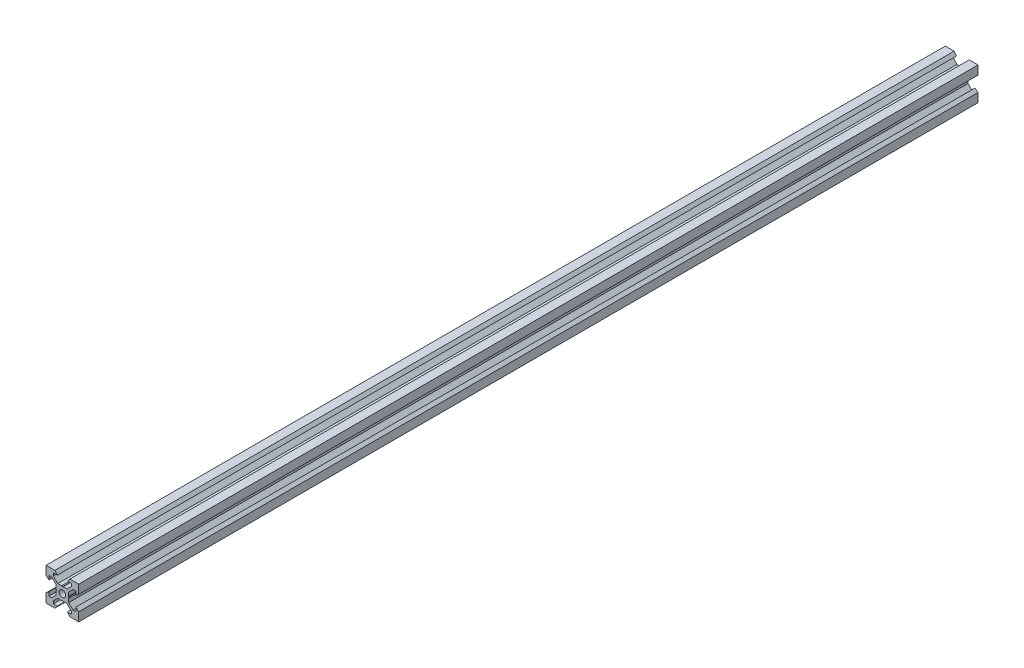
SolidWorks part; units mm, degrees
ref_plane "Front Plane" through (0, 0, 0) normal (0, 0, 1) x (1, 0, 0)
ref_plane "Top Plane" through (0, 0, 0) normal (0, 1, 0) x (1, 0, 0)
ref_plane "Right Plane" through (0, 0, 0) normal (1, 0, 0) x (0, 0, -1)
sketch "Sketch1" plane through (0, 0, 0) normal (0, 0, 1) x (1, 0, 0)
  line L0 (10, 10) -> (4.6104, 10) construction
  line L1 (10, 10) -> (10, 4.6104) construction
  line L2 (10, -10) -> (10, -4.6104) construction
  line L3 (10, -10) -> (4.6104, -10) construction
  line L4 (10, 10) -> (10, 4.6104)
  line L5 (6.5607, 5.5) -> (8.2, 5.5)
  line L6 (5.5, 8.2) -> (5.5, 6.5607)
  line L7 (10, 10) -> (4.6104, 10)
  line L8 (10, 10) -> (10, 4.6104)
  line L9 (6.5607, 5.5) -> (3.9, 2.8393)
  line L10 (5.5, 6.5607) -> (2.8393, 3.9)
  line L11 (10, 4.6104) -> (8.2, 3.1)
  line L12 (4.6104, 10) -> (3.1, 8.2)
  line L13 (8.2, 3.1) -> (8.2, 5.5)
  line L14 (3.1, 8.2) -> (5.5, 8.2)
  line L15 (-6.5607, 5.5) -> (-8.2, 5.5)
  line L16 (6.5607, -5.5) -> (8.2, -5.5)
  line L17 (3.1, -8.2) -> (5.5, -8.2)
  line L18 (8.2, -3.1) -> (8.2, -5.5)
  line L19 (4.6104, -10) -> (3.1, -8.2)
  line L20 (10, -4.6104) -> (8.2, -3.1)
  line L21 (0.5196, -3.9) -> (0, -3.6)
  line L22 (0.5196, 3.9) -> (0, 3.6)
  line L23 (3.6, 0) -> (3.9, -0.5196)
  line L24 (3.9, 0.5196) -> (3.6, 0)
  line L25 (3.9, 0.5196) -> (3.9, 2.8393)
  line L26 (2.8393, 3.9) -> (0.5196, 3.9)
  line L27 (3.9, -2.8393) -> (3.9, -0.5196)
  line L28 (2.8393, -3.9) -> (0.5196, -3.9)
  line L29 (5.5, -6.5607) -> (2.8393, -3.9)
  line L30 (6.5607, -5.5) -> (3.9, -2.8393)
  line L31 (10, -10) -> (10, -4.6104)
  line L32 (10, -10) -> (4.6104, -10)
  line L33 (5.5, -8.2) -> (5.5, -6.5607)
  line L34 (-6.5607, -5.5) -> (-8.2, -5.5)
  line L35 (10, -10) -> (10, -4.6104)
  line L36 (0, 0) -> (0, 8.2) construction
  line L37 (-10, -10) -> (-4.6104, -10) construction
  line L38 (-10, -10) -> (-10, -4.6104) construction
  line L39 (-10, 10) -> (-10, 4.6104) construction
  line L40 (-10, 10) -> (-4.6104, 10) construction
  line L41 (-10, -10) -> (-10, -4.6104)
  line L43 (-5.5, -8.2) -> (-5.5, -6.5607)
  line L44 (-10, -10) -> (-4.6104, -10)
  line L45 (-10, -10) -> (-10, -4.6104)
  line L46 (-6.5607, -5.5) -> (-3.9, -2.8393)
  line L47 (-5.5, -6.5607) -> (-2.8393, -3.9)
  line L48 (-2.8393, -3.9) -> (-0.5196, -3.9)
  line L49 (-3.9, -2.8393) -> (-3.9, -0.5196)
  line L50 (-2.8393, 3.9) -> (-0.5196, 3.9)
  line L51 (-3.9, 0.5196) -> (-3.9, 2.8393)
  line L52 (-3.9, 0.5196) -> (-3.6, 0)
  line L53 (-3.6, 0) -> (-3.9, -0.5196)
  line L54 (-0.5196, 3.9) -> (0, 3.6)
  line L55 (-0.5196, -3.9) -> (0, -3.6)
  line L56 (-10, -4.6104) -> (-8.2, -3.1)
  line L57 (-4.6104, -10) -> (-3.1, -8.2)
  line L58 (-8.2, -3.1) -> (-8.2, -5.5)
  line L59 (-3.1, -8.2) -> (-5.5, -8.2)
  line L60 (-10, -10) -> (10, -10) construction
  line L61 (-10, -10) -> (-10, 10) construction
  line L62 (-3.1, 8.2) -> (-5.5, 8.2)
  line L63 (-8.2, 3.1) -> (-8.2, 5.5)
  line L64 (-4.6104, 10) -> (-3.1, 8.2)
  line L65 (-10, 4.6104) -> (-8.2, 3.1)
  line L66 (-5.5, 6.5607) -> (-2.8393, 3.9)
  line L67 (-6.5607, 5.5) -> (-3.9, 2.8393)
  line L68 (-10, 10) -> (-10, 4.6104)
  line L69 (-10, 10) -> (-4.6104, 10)
  line L70 (-5.5, 8.2) -> (-5.5, 6.5607)
  line L71 (-10, 10) -> (10, 10) construction
  line L72 (-10, 10) -> (-10, 4.6104)
  line L73 (10, -10) -> (10, 10) construction
  line L74 (-10, -10) -> (10, 10) construction
  line L75 (-10, 10) -> (10, -10) construction
  circle A0 centre (0, 0) radius 2
  dimension "D7" = 4
  dimension "D1" = 20
  dimension "D2" = 5.3896
  dimension "D3" = 4.5
  dimension "D4" = 50
  dimension "D5" = 1.8
  dimension "D6" = 1.5104
  dimension "D8" = 5.5
  dimension "D9" = 120
  dimension "D10" = 0.3
  dimension "D11" = 2.3197
  dimension "D12" = 7.8
  dimension "D13" = 7.8
  dimension "D14" = 1.5
  dimension "D15" = 2.6607
extrude "Boss-Extrude1" add sketch "Sketch1" along normal mid plane 550 contours L70 L62 L64 L69 L68 L65 L63 L15 L67 L51 L52 L53 L49 L46 L34 L58 L56 L41 L44 L57 L59 L43 L47 L48 L55 L21 L28 L29 L33 L17 L19 L32 L31 L20 L18 L16 L30 L27 L23 L24 L25 L9 L5 L13 L11 L4 L7 L12 L14 L6 L10
